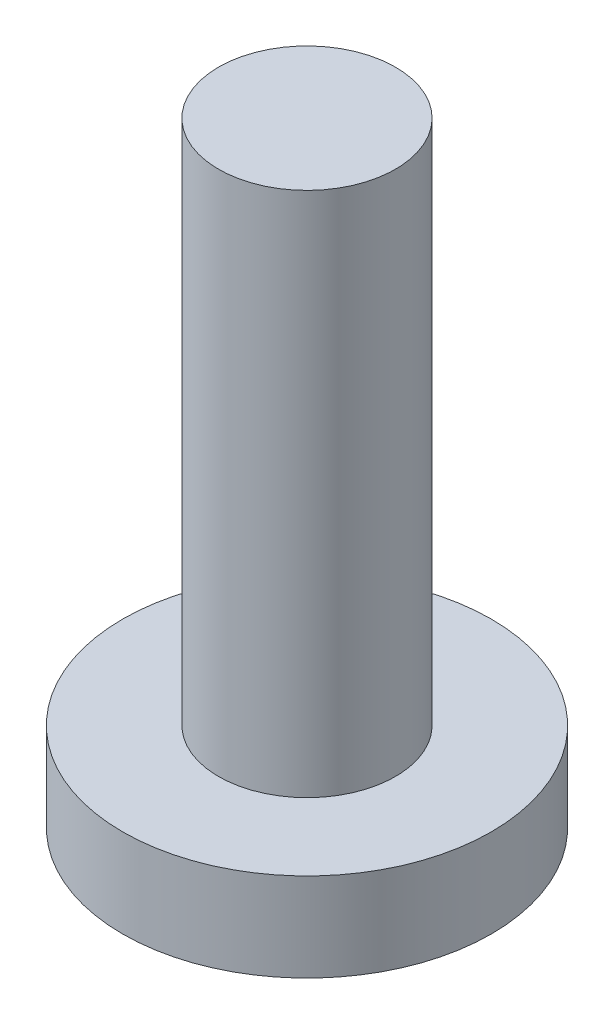
SolidWorks part; units mm, degrees
ref_plane "Front Plane" through (0, 0, 0) normal (0, 0, 1) x (1, 0, 0)
ref_plane "Top Plane" through (0, 0, 0) normal (0, 1, 0) x (1, 0, 0)
ref_plane "Right Plane" through (0, 0, 0) normal (1, 0, 0) x (0, 0, -1)
sketch "Sketch1" plane through (0, 0, 0) normal (0, 0, 1) x (1, 0, 0)
  line L0 (0, 0) -> (0, -7.9375)
  line L1 (0, -7.9375) -> (2.3813, -7.9375)
  line L2 (2.3813, -7.9375) -> (2.3813, -6.7945)
  line L3 (2.3813, -6.7945) -> (1.143, -6.7945)
  line L4 (1.143, -6.7945) -> (1.143, 0)
  line L5 (1.143, 0) -> (0, 0)
  dimension "D1" = 1.143
  dimension "D2" = 1.143
  dimension "D3" = 7.9375
  dimension "D4" = 2.3813
revolve "Revolve1" add sketch "Sketch1" angle 360 about L0
